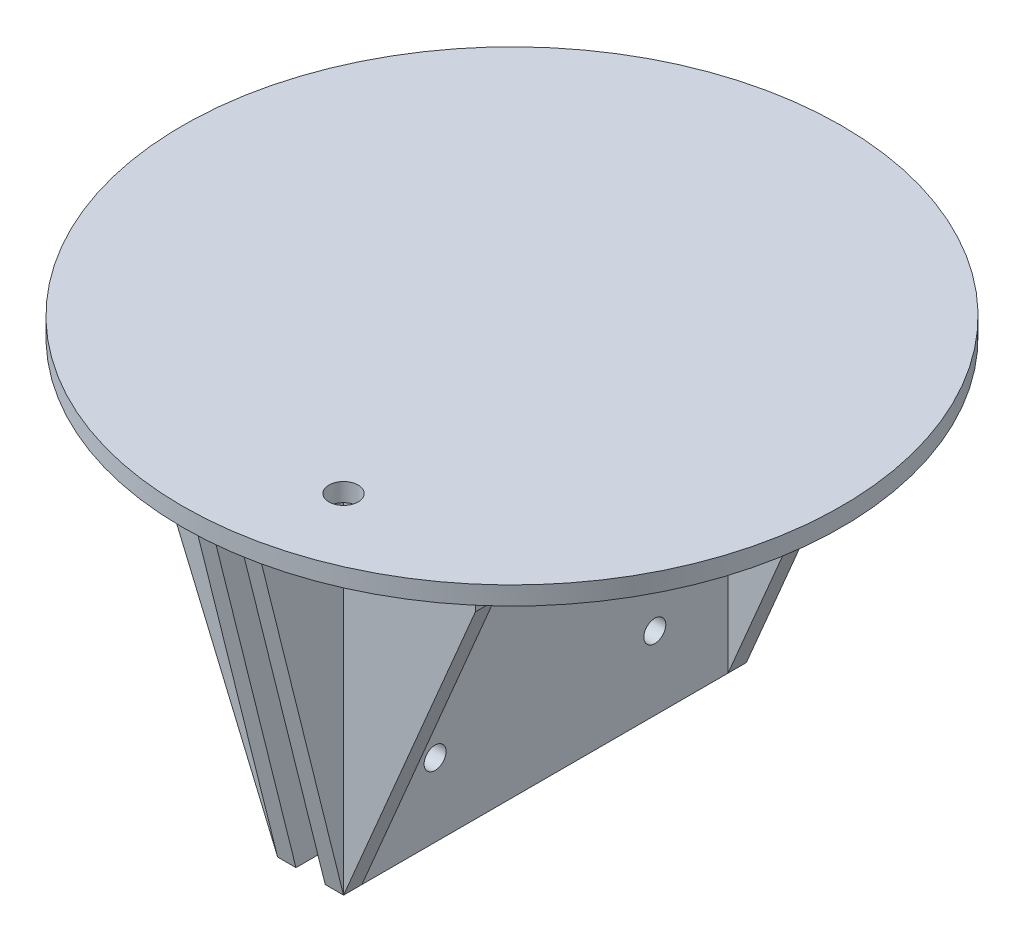
SolidWorks part; units mm, degrees
ref_plane "Front Plane" through (0, 0, 0) normal (0, 0, 1) x (1, 0, 0)
ref_plane "Top Plane" through (0, 0, 0) normal (0, 1, 0) x (1, 0, 0)
ref_plane "Right Plane" through (0, 0, 0) normal (1, 0, 0) x (0, 0, -1)
sketch "Sketch1" plane through (0, 0, 0) normal (0, 1, 0) x (1, 0, 0)
  circle A0 centre (0, 0) radius 90
  dimension "D1" = 180
extrude "Boss-Extrude1" add sketch "Sketch1" along normal blind 5
sketch "Sketch2" plane through (0, 0, 0) normal (0, -1, 0) x (-1, 0, 0)
  line L0 (90, 0) -> (-90, 0) construction
  line L5 (0, 0) -> (0, -90) construction
  line L6 (-45, -50) -> (-45, -55)
  line L7 (-45, -55) -> (45, -55)
  line L9 (-45, -50) -> (45, -50)
  line L10 (45, -55) -> (45, -50)
  circle A0 centre (0, 0) radius 90 construction
  point P11 (0, 0)
  point P13 (0, -55)
  dimension "D1" = 5
  dimension "D2" = 90
  dimension "D3" = 50
extrude "Boss-Extrude2" add sketch "Sketch2" along normal blind 100
sketch "Sketch3" plane through (0, 0, 55) normal (0, 0, 1) x (1, 0, 0)
  line L0 (45, -15) -> (9, -100)
  line L1 (45, -100) -> (45, 0) construction
  line L2 (45, -100) -> (-45, -100) construction
  line L3 (45, -100) -> (9, -100)
  line L4 (45, -15) -> (45, -100)
  dimension "D1" = 36
  dimension "D2" = 85
extrude "Cut-Extrude1" cut sketch "Sketch3" against normal blind 100
mirror "Mirror1" about plane through (0, 0, 0) normal (1, 0, 0) of "Cut-Extrude1"
sketch "Sketch4" plane through (0, 0, 55) normal (0, 0, 1) x (1, 0, 0)
  line L5 (0, 0) -> (0, -100) construction
  line L6 (45, 0) -> (-45, 0) construction
  line L7 (9, -100) -> (-9, -100) construction
  line L9 (-4, -100) -> (4, -100)
  line L10 (-4, -100) -> (-4, -50)
  line L11 (-4, -50) -> (4, -50)
  line L12 (4, -100) -> (4, -50)
  dimension "D1" = 8
  dimension "D2" = 50
extrude "Cut-Extrude2" cut sketch "Sketch4" against normal through all
mirror "Mirror2" about plane through (0, 0, 0) normal (0, 0, 1) of "Boss-Extrude2", "Cut-Extrude1", "Mirror1", "Cut-Extrude2"
sketch "Sketch5" plane through (0, 0, 0) normal (0, -1, 0) x (1, 0, 0)
  line L1 (-9, 50) -> (-4, 50)
  line L2 (-9, 50) -> (-9, -50)
  line L3 (-9, -50) -> (-4, -50)
  line L4 (-4, 50) -> (-4, -50)
extrude "Boss-Extrude3" add sketch "Sketch5" along normal blind 100
mirror "Mirror3" about plane through (0, 0, 0) normal (1, 0, 0) of "Boss-Extrude3"
ref_plane "Plane1" through (-6.5, 0, 0) normal (1, 0, 0) x (0, 0, -1)
sketch "Sketch6" plane through (-6.5, 0, 0) normal (1, 0, 0) x (0, 0, -1)
  line L0 (-55, -100) -> (-55, 0)
  line L1 (-55, 0) -> (-80, 0)
  line L2 (-90, 0) -> (90, 0) construction
  line L3 (-80, 0) -> (-55, -100)
  dimension "D1" = 25
extrude "Boss-Extrude4" add sketch "Sketch6" along normal blind 2.5 and the other way blind 2.5
mirror "Mirror4" about plane through (0, 0, 0) normal (1, 0, 0) of "Boss-Extrude4"
mirror "Mirror5" about plane through (0, 0, 0) normal (0, 0, 1) of "Mirror4", "Boss-Extrude4"
sketch "Sketch7" plane through (9, 0, 0) normal (1, 0, 0) x (0, 0, -1)
  line L0 (-50, -100) -> (50, -100) construction
  line L1 (-50, -100) -> (-50, 0) construction
  circle A0 centre (-30, -80) radius 3
  dimension "D1" = 6
  dimension "D2" = 20
  dimension "D3" = 20
extrude "Cut-Extrude3" cut sketch "Sketch7" against normal through all
mirror "Mirror6" about plane through (0, 0, 0) normal (0, 0, 1) of "Cut-Extrude3"
sketch "Sketch8" plane through (0, 0, 0) normal (0, -1, 0) x (1, 0, 0)
  line L0 (45, 55) -> (9, 55) construction
  line L1 (9, 55) -> (9, 80) construction
  circle A0 centre (19, 65) radius 4
  dimension "D1" = 8
  dimension "D2" = 10
  dimension "D3" = 10
extrude "Cut-Extrude4" cut sketch "Sketch8" against normal through all
